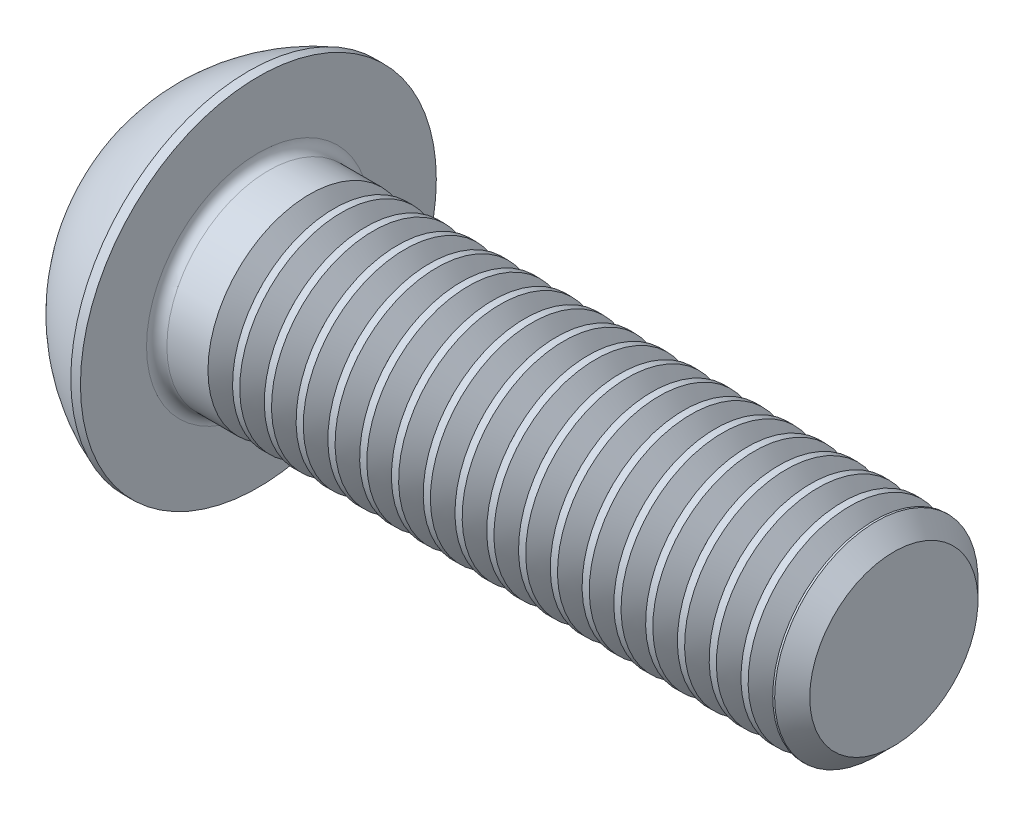
SolidWorks part; units mm, degrees
ref_plane "Plane1" through (0, 0, 0) normal (0, 0, 1) x (1, 0, 0)
ref_plane "Plane2" through (0, 0, 0) normal (0, 1, 0) x (1, 0, 0)
ref_plane "Plane3" through (0, 0, 0) normal (1, 0, 0) x (0, 0, -1)
sketch "BodySke" plane through (0, 0, 0) normal (0, 0, 1) x (1, 0, 0)
  line L0 (29.4, 0) -> (29.4, 3.3095)
  line L1 (28.7095, 4) -> (4.4, 4)
  line L2 (4.4, 4) -> (4.4, 7)
  line L3 (4.4, 7) -> (4.02, 7)
  line L4 (0, 0) -> (101.6, 0) construction
  line L5 (4.4, -7) -> (4.02, -7) construction
  line L6 (55.6768, -4) -> (4.4, -4) construction
  line L7 (29.4, 0) -> (0, 0)
  line L8 (0, 3.5) -> (0, -3.5) construction
  line L9 (0, 0) -> (0, 3.5)
  line L10 (29.4, 3.3095) -> (28.7095, 4)
  line L11 (29.4, -3.3095) -> (28.7095, -4) construction
  line L12 (5.65, 9.525) -> (5.65, -4) construction
  line L13 (4.4, 9.525) -> (4.4, -4) construction
  arc A1 (0, 3.5) -> (4.02, 7) centre (6.5809, 0) cw
  dimension "Diameter" = 8
  dimension "Length" = 25
  dimension "Head_dia" = 14
  dimension "D1" = 7
  dimension "Head_ht" = 4.4
  dimension "Head_side_ht" = 0.38
  dimension "Minor_dia" = 6.619
  dimension "Body_ch_ang" = 45
  dimension "Advance" = 1.25
  dimension "Thread_nom" = 25
revolve "BaseBody" add sketch "BodySke" angle 360 about L4
cosmetic thread "ThreadCosmetic" [suppressed] parameters "Thread_length"=22.5, "Thread_minor"=6.619
fillet "Fillet1" radius 0.4 1 edges at (4.4, 0, 4)
sketch "Sketch2" plane through (0, 0, 0) normal (0, 0, 1) x (1, 0, 0)
  line L0 (0, 2.5) -> (2.6, 2.5)
  line L1 (2.6, 2.5) -> (4.0434, 0)
  line L3 (4.0434, 0) -> (0, 0)
  line L4 (0, 0) -> (0, 2.5)
  line L5 (0, -2.5) -> (2.6, -2.5) construction
  line L6 (0, 0) -> (47.625, 0) construction
  dimension "D2" = 60
  dimension "PreBroach_depth" = 2.6
  dimension "PreBroach_dia" = 5
revolve "PreBroach" cut sketch "Sketch2" angle 360 about L6
sketch "Sketch3" plane through (0, 0, 0) normal (1, 0, 0) x (0, 0, -1)
  line L0 (-2.5, -1.4434) -> (-2.5, 1.4434)
  line L1 (-2.5, 1.4434) -> (0, 2.8868)
  line L2 (0, 2.8868) -> (2.5, 1.4434)
  line L3 (2.5, 1.4434) -> (2.5, -1.4434)
  line L4 (2.5, -1.4434) -> (0, -2.8868)
  line L5 (0, -2.8868) -> (-2.5, -1.4434)
  dimension "Hex_size" = 5
  dimension "D3" = 5
  dimension "D1" = 2.5
  dimension "D2" = 2.5
extrude "Hex" cut sketch "Sketch3" along normal blind 2.6
sketch "ThdSchSke" plane through (0, 0, 0) normal (0, 0, 1) x (1, 0, 0)
  line L0 (6.9, -3.3095) -> (6.4165, -4)
  line L1 (6.9, -3.3095) -> (7.3835, -4)
  line L2 (7.3835, -4) -> (7.3835, -5)
  line L3 (-3.175, 0) -> (5.1513, 0) construction
  line L5 (7.3835, -5) -> (6.4165, -5)
  line L6 (6.4165, -5) -> (6.4165, -4)
  dimension "Diameter" = 8
  dimension "Thread_minor" = 6.619
  dimension "SideAngle" = 55
  dimension "VeeAngle" = 70
  dimension "Overcut" = 10
  dimension "Start" = 6.9
revolve "ThreadSchematic" cut sketch "ThdSchSke" angle 360 about L3
pattern_linear "ThdSchPat" count 18 spacing 1.25 along (1, 0, 0) of "ThreadSchematic"
equation "\"D1@BodySke\" = \"Head_dia@BodySke\" * .5"
equation "\"Thread_minor@ThreadCosmetic\" = \"Minor_dia@BodySke\""
equation "\"D1@Sketch3\" = \"Hex_size@Sketch3\" / 2"
equation "\"D2@Sketch3\" = \"D1@Sketch3\""
equation "\"D3@Sketch3\" = \"Hex_size@Sketch3\""
equation "\"Thread_length@ThreadCosmetic\" = ((sgn( (\"Length@BodySke\" - \"Advance@BodySke\" * 2.0) - \"Thread_nom@BodySke\" )-1)*( (\"Length@BodySke\" - \"Advance@BodySke\" * 2.0) - \"Thread_nom@BodySke\" ))/-2+ \"Thread_nom@BodySke\""
equation "\"Thread_minor@ThdSchSke\" = \"Minor_dia@BodySke\""
equation "\"Diameter@ThdSchSke\" = \"Diameter@BodySke\""
equation "\"Overcut@ThdSchSke\" = \"Diameter@BodySke\" * 1.25"
equation "\"Start@ThdSchSke\" = \"Head_ht@BodySke\" + \"Length@BodySke\" - \"Thread_length@ThreadCosmetic\"  '---Non-countersunk---"
equation "\"Num_threads@ThdSchPat\" = int( \"Thread_length@ThreadCosmetic\" / \"Advance@BodySke\" + 0.999 )  + 1"
equation "\"Advance@ThdSchPat\" = \"Thread_length@ThreadCosmetic\" /  (\"Num_threads@ThdSchPat\" - 1) 'relax it"
equation "\"Num_threads@ThdSchPat\" = \"Num_threads@ThdSchPat\" - sgn( \"Num_threads@ThdSchPat\" - 1) '---chamfered tips only---"
